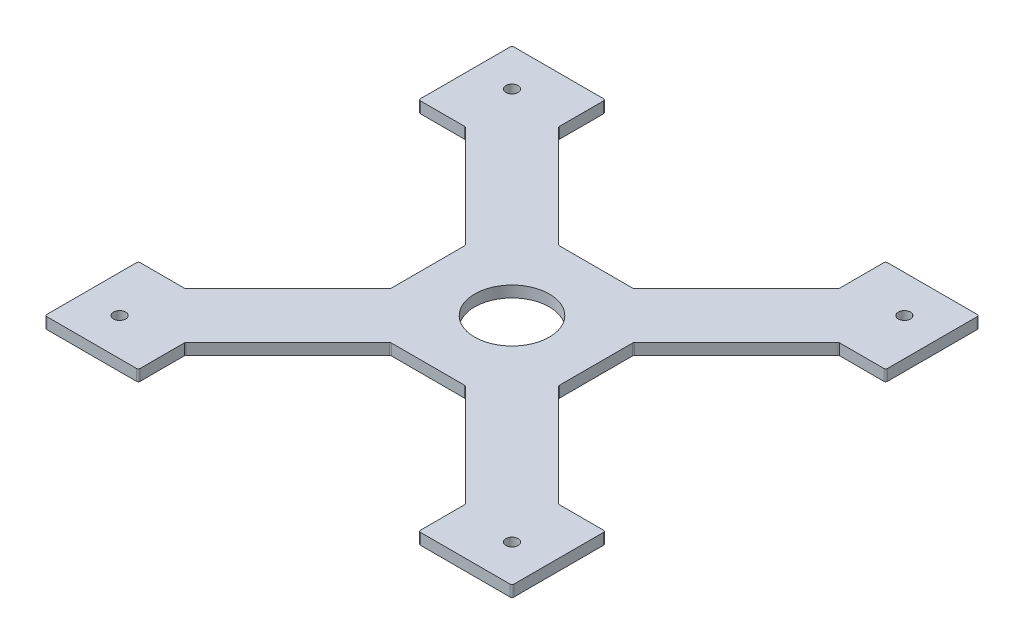
SolidWorks part; units mm, degrees
material "Beech"
ref_plane "Спереди" through (0, 0, 0) normal (0, 0, 1) x (1, 0, 0)
ref_plane "Сверху" through (0, 0, 0) normal (0, 1, 0) x (1, 0, 0)
ref_plane "Справа" through (0, 0, 0) normal (1, 0, 0) x (0, 0, -1)
sketch "Sketch1" plane through (0, 0, 0) normal (0, 1, 0) x (1, 0, 0)
  line L1 (0, 0) -> (250, 0)
  line L2 (0, 0) -> (0, 250)
  line L3 (0, 250) -> (250, 250)
  line L4 (250, 0) -> (250, 250)
  dimension "D1" = 250
  dimension "D2" = 250
extrude "table" add sketch "Sketch1" against normal blind 6
sketch "Sketch2" plane through (0, 0, 0) normal (0, 1, 0) x (1, 0, 0)
  line L0 (0, 200) -> (25, 200)
  line L1 (0, 250) -> (0, 0) construction
  line L2 (25, 200) -> (80, 145)
  line L3 (80, 145) -> (80, 105)
  line L4 (80, 105) -> (25, 50)
  line L5 (25, 50) -> (0, 50)
  line L6 (50, 250) -> (50, 225)
  line L7 (250, 250) -> (0, 250) construction
  line L8 (50, 225) -> (105, 170)
  line L9 (105, 170) -> (145, 170)
  line L10 (145, 170) -> (200, 225)
  line L11 (200, 225) -> (200, 250)
  line L12 (250, 200) -> (225, 200)
  line L13 (250, 0) -> (250, 250) construction
  line L14 (225, 200) -> (170, 145)
  line L15 (170, 145) -> (170, 105)
  line L16 (170, 105) -> (225, 50)
  line L17 (225, 50) -> (250, 50)
  line L18 (50, 0) -> (50, 25)
  line L19 (0, 0) -> (250, 0) construction
  line L20 (50, 25) -> (105, 80)
  line L21 (105, 80) -> (145, 80)
  line L22 (145, 80) -> (200, 25)
  line L23 (200, 25) -> (200, 0)
  line L24 (0, 200) -> (0, 50)
  line L25 (50, 0) -> (200, 0)
  line L26 (250, 50) -> (250, 200)
  line L27 (200, 250) -> (50, 250)
  circle A0 centre (20, 230) radius 3.25
  circle A1 centre (230, 230) radius 3.25
  circle A2 centre (230, 20) radius 3.25
  circle A3 centre (20, 20) radius 3.25
  point P40 (125, 80)
  point P41 (170, 125)
  dimension "D8" = 210
  dimension "D9" = 105
  dimension "D11" = 6.5
  dimension "D1" = 50
  dimension "D2" = 50
  dimension "D3" = 50
  dimension "D4" = 50
  dimension "D5" = 80
  dimension "D6" = 40
  dimension "D7" = 210
  dimension "D10" = 105
extrude "cut" cut sketch "Sketch2" against normal blind 6
fillet "Fillet1" radius 1 28 edges at (200, -3, -225) (200, -3, -250) (250, -3, -250) (250, -3, -200) (225, -3, -200) (225, -3, -50) (250, -3, -50) (250, -3, 0) (200, -3, 0) (200, -3, -25) (145, -3, -80) (0, -3, -50) (0, -3, 0) (50, -3, 0) (50, -3, -25) (25, -3, -50) (105, -3, -80) (80, -3, -105) (170, -3, -105) (170, -3, -145) (145, -3, -170) (105, -3, -170) (80, -3, -145) (25, -3, -200) (50, -3, -225) (50, -3, -250) (0, -3, -250) (0, -3, -200)
sketch "Sketch3" plane through (0, 0, 0) normal (0, 1, 0) x (1, 0, 0)
  line L0 (80, 105.4142) -> (80, 144.5858) construction
  line L1 (105.4142, 170) -> (144.5858, 170) construction
  circle A0 centre (125, 125) radius 20
  point P2 (80, 125)
  point P3 (125, 170)
  dimension "D1" = 40
extrude "lite" cut sketch "Sketch3" against normal through all
